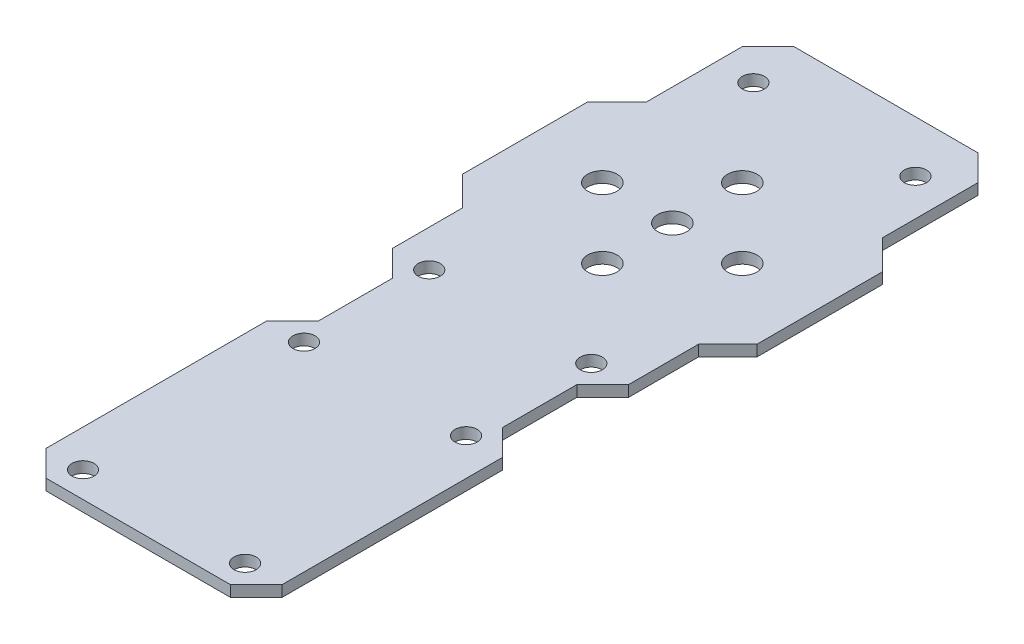
SolidWorks part; units mm, degrees
material "Hexcel AS4C (3000 丝)"
ref_plane "前视基准面" through (0, 0, 0) normal (0, 0, 1) x (1, 0, 0)
ref_plane "上视基准面" through (0, 0, 0) normal (0, 1, 0) x (1, 0, 0)
ref_plane "右视基准面" through (0, 0, 0) normal (1, 0, 0) x (0, 0, -1)
sketch "草图1" plane through (0, 0, 0) normal (0, 1, 0) x (1, 0, 0)
  line L0 (0, 0) -> (0, 36) construction
  line L2 (19.9892, 17.0108) -> (19.9892, 34.0323)
  line L3 (16.0215, 3.543) -> (16.0215, 13.043)
  line L4 (16.0215, 13.043) -> (19.9892, 17.0108)
  line L5 (19.9892, 34.0323) -> (15.9941, 38.0274)
  line L6 (15.9941, 38.0274) -> (15.9941, 51.002)
  line L7 (0, 25.5) -> (9.5, 25.5) construction
  line L8 (0, 3.5) -> (11, 3.5) construction
  line L21 (12.5108, 0.0323) -> (16.0215, 3.543)
  line L22 (-12.5108, 0.0323) -> (-16.0215, 3.543)
  line L34 (-15.9941, 38.0274) -> (-15.9941, 51.002)
  line L35 (-19.9892, 34.0323) -> (-15.9941, 38.0274)
  line L36 (-16.0215, 13.043) -> (-19.9892, 17.0108)
  line L37 (-16.0215, 3.543) -> (-16.0215, 13.043)
  line L38 (-19.9892, 17.0108) -> (-19.9892, 34.0323)
  line L39 (12.5108, 0.0323) -> (12.5108, -10.0323)
  line L40 (12.5108, -10.0323) -> (16.0215, -13.543)
  line L41 (16.0215, -13.543) -> (16.0215, -43.5)
  line L45 (-16.0215, -13.543) -> (-16.0215, -43.5)
  line L46 (-12.5108, -10.0323) -> (-16.0215, -13.543)
  line L47 (-12.5108, 0.0323) -> (-12.5108, -10.0323)
  line L48 (-15.9941, 51.002) -> (-12.4961, 54.5)
  line L49 (-12.4961, 54.5) -> (12.4961, 54.5)
  line L50 (12.4961, 54.5) -> (15.9941, 51.002)
  line L51 (16.0215, -43.5) -> (12.5215, -47)
  line L52 (12.5215, -47) -> (-12.5215, -47)
  line L53 (-16.0215, -43.5) -> (-12.5215, -47)
  circle A0 centre (0, 25.5) radius 2
  circle A1 centre (9.5, 25.5) radius 2
  circle A5 centre (11, 3.5) radius 1.5
  circle A6 centre (11, 47.5) radius 1.5
  circle A7 centre (-11, 47.5) radius 1.5
  circle A8 centre (-11, 3.5) radius 1.5
  circle A9 centre (11, -13.5) radius 1.5
  circle A10 centre (11, -43.5) radius 1.5
  circle A11 centre (-11, -13.5) radius 1.5
  circle A12 centre (-11, -43.5) radius 1.5
  circle A13 centre (0, 16) radius 2
  circle A14 centre (-9.5, 25.5) radius 2
  circle A15 centre (0, 35) radius 2
  point P5 (16, 0)
  point P7 (0, 25.5)
  point P14 (19.9892, 34.0323)
  point P16 (0, 3.5)
  point P64 (-19.9892, 34.0323)
  point P65 (-16, 0)
  dimension "D1" = 4
extrude "凸台-拉伸1" add sketch "草图1" along normal blind 1.5
